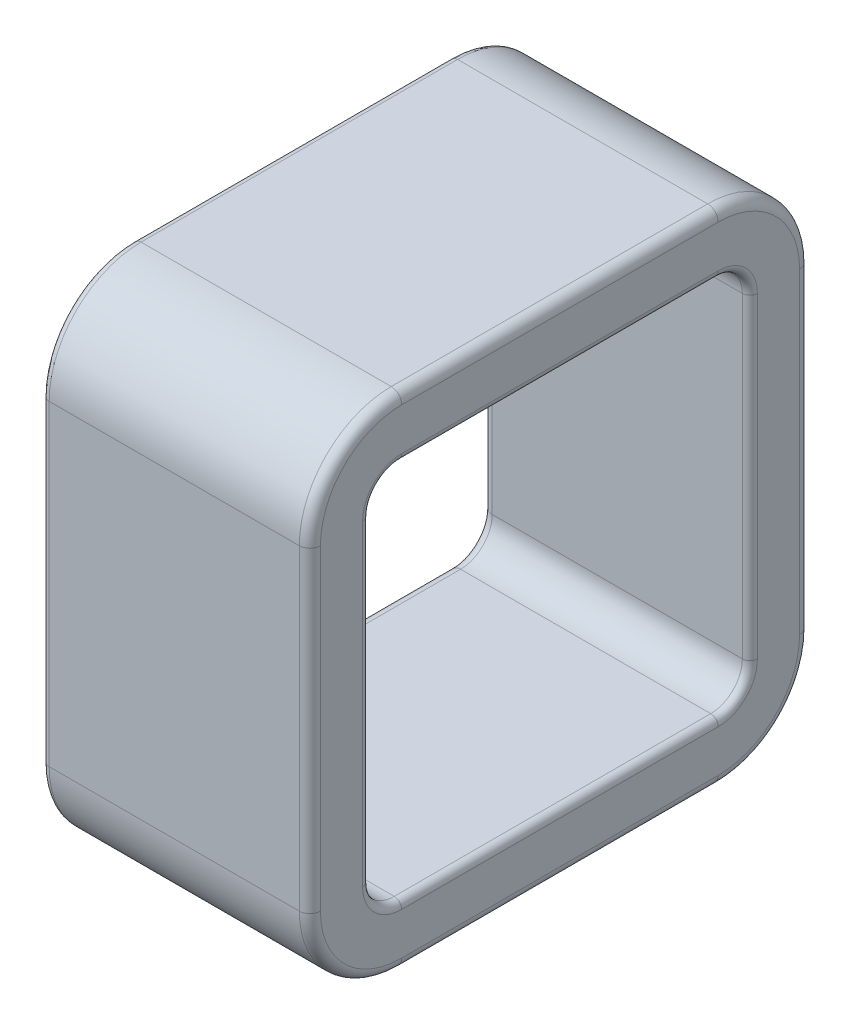
SolidWorks part; units mm, degrees
ref_plane "Front Plane" through (0, 0, 0) normal (0, 0, 1) x (1, 0, 0)
ref_plane "Top Plane" through (0, 0, 0) normal (0, 1, 0) x (1, 0, 0)
ref_plane "Right Plane" through (0, 0, 0) normal (1, 0, 0) x (0, 0, -1)
ref_plane "Plane1" through (72.6, 0, 0) normal (1, 0, 0) x (0, 0, -1)
ref_plane "Plane2" through (0, 8.25, 0) normal (0, 1, 0) x (1, 0, 0)
sketch "Sketch1" plane through (72.6, 0, 0) normal (1, 0, 0) x (0, 0, -1)
  line L0 (-27.5, 17.5) -> (-27.5, -3.5) construction
  line L1 (-25.5, -5.5) -> (-4.5, -5.5) construction
  line L2 (-2.5, 17.5) -> (-2.5, -3.5) construction
  line L3 (-25.5, 19.5) -> (-4.5, 19.5) construction
  line L4 (-27.5, 17.5) -> (-27.5, -3.5) construction
  line L5 (-25.5, -5.5) -> (-4.5, -5.5) construction
  line L6 (-2.5, 17.5) -> (-2.5, -3.5) construction
  line L7 (-25.5, 19.5) -> (-4.5, 19.5) construction
  line L8 (-27.6, 17.5) -> (-27.6, -3.5)
  line L9 (-25.5, -5.6) -> (-4.5, -5.6)
  line L10 (-2.4, 17.5) -> (-2.4, -3.5)
  line L11 (-25.5, 19.6) -> (-4.5, 19.6)
  line L16 (-31.6, 17.5) -> (-31.6, -3.5)
  line L17 (-28.6, 21) -> (-1.4, 21) construction
  line L18 (-31.6, 18) -> (-31.6, -4) construction
  line L19 (-28.6, -7) -> (-1.4, -7) construction
  line L20 (1.6, 18) -> (1.6, -4) construction
  line L21 (-25.5, -9.6) -> (-4.5, -9.6)
  line L22 (1.6, 17.5) -> (1.6, -3.5)
  line L23 (-25.5, 23.6) -> (-4.5, 23.6)
  arc A0 (-27.5, -3.5) -> (-25.5, -5.5) centre (-25.5, -3.5) ccw construction
  arc A1 (-4.5, -5.5) -> (-2.5, -3.5) centre (-4.5, -3.5) ccw construction
  arc A2 (-2.5, 17.5) -> (-4.5, 19.5) centre (-4.5, 17.5) ccw construction
  arc A3 (-25.5, 19.5) -> (-27.5, 17.5) centre (-25.5, 17.5) ccw construction
  arc A4 (-27.5, -3.5) -> (-25.5, -5.5) centre (-25.5, -3.5) ccw construction
  arc A5 (-4.5, -5.5) -> (-2.5, -3.5) centre (-4.5, -3.5) ccw construction
  arc A6 (-2.5, 17.5) -> (-4.5, 19.5) centre (-4.5, 17.5) ccw construction
  arc A7 (-25.5, 19.5) -> (-27.5, 17.5) centre (-25.5, 17.5) ccw construction
  arc A8 (-27.6, -3.5) -> (-25.5, -5.6) centre (-25.5, -3.5) ccw
  arc A9 (-4.5, -5.6) -> (-2.4, -3.5) centre (-4.5, -3.5) ccw
  arc A10 (-2.4, 17.5) -> (-4.5, 19.6) centre (-4.5, 17.5) ccw
  arc A11 (-25.5, 19.6) -> (-27.6, 17.5) centre (-25.5, 17.5) ccw
  arc A16 (-31.6, -4) -> (-28.6, -7) centre (-28.6, -4) ccw construction
  arc A17 (-1.4, -7) -> (1.6, -4) centre (-1.4, -4) ccw construction
  arc A18 (1.6, 18) -> (-1.4, 21) centre (-1.4, 18) ccw construction
  arc A19 (-28.6, 21) -> (-31.6, 18) centre (-28.6, 18) ccw construction
  arc A20 (-31.6, -3.5) -> (-25.5, -9.6) centre (-25.5, -3.5) ccw
  arc A21 (-4.5, -9.6) -> (1.6, -3.5) centre (-4.5, -3.5) ccw
  arc A22 (1.6, 17.5) -> (-4.5, 23.6) centre (-4.5, 17.5) ccw
  arc A23 (-25.5, 23.6) -> (-31.6, 17.5) centre (-25.5, 17.5) ccw
  dimension "D6" = 3
  dimension "D2" = 1.5
  dimension "D3" = 1.5
  dimension "D4" = 4
  dimension "D1" = 0.1
extrude "Boss-Extrude1" add sketch "Sketch1" against normal offset from surface 0.2 and the other way blind 12
sketch "Sketch2" plane through (0, 8.25, 0) normal (0, 1, 0) x (1, 0, 0)
  line L0 (-0.1, -3) -> (-0.1, -27) construction
  line L1 (3, -30.1) -> (62, -30.1) construction
  line L2 (65.1, -27) -> (65.1, -3) construction
  line L3 (62, 0.1) -> (3, 0.1) construction
  line L4 (66.6, 1.6) -> (-1.6, 1.6) construction
  line L5 (-1.6, 1.6) -> (-1.6, -31.6) construction
  line L6 (66.6, 1.6) -> (66.6, -31.6) construction
  line L7 (-1.6, -31.6) -> (66.6, -31.6) construction
  line L8 (-0.1, -3) -> (-0.1, -27)
  line L9 (3, -30.1) -> (62, -30.1)
  line L10 (65.1, -27) -> (65.1, -3)
  line L11 (62, 0.1) -> (3, 0.1)
  line L12 (66.6, 1.6) -> (-1.6, 1.6)
  line L13 (-1.6, 1.6) -> (-1.6, -31.6)
  line L14 (66.6, 1.6) -> (66.6, -31.6)
  line L15 (-1.6, -31.6) -> (66.6, -31.6)
  line L16 (0.65, -3) -> (-1.6, -3)
  line L17 (0.65, -27) -> (-1.6, -27)
  line L20 (57.6, 0.1) -> (57.6, 1.6) construction
  line L21 (7.4, 0.1) -> (7.4, 1.6) construction
  line L23 (59.1, -29.35) -> (59.1, -31.6)
  line L24 (6.4, -29.35) -> (6.4, -31.6)
  line L25 (18.9, -30.1) -> (18.9, -31.6)
  line L26 (37.1, -30.1) -> (37.1, -31.6)
  line L27 (3, -29.35) -> (62, -29.35)
  line L28 (64.35, -27) -> (64.35, -3)
  line L29 (62, -0.65) -> (3, -0.65)
  line L30 (64.35, -27) -> (66.6, -27)
  line L31 (64.35, -3) -> (66.6, -3)
  line L35 (57.6, 0.1) -> (57.6, 1.6)
  line L36 (7.4, 0.1) -> (7.4, 1.6)
  arc A0 (3, 0.1) -> (-0.1, -3) centre (3, -3) ccw construction
  arc A1 (-0.1, -27) -> (3, -30.1) centre (3, -27) ccw construction
  arc A2 (62, -30.1) -> (65.1, -27) centre (62, -27) ccw construction
  arc A3 (65.1, -3) -> (62, 0.1) centre (62, -3) ccw construction
  arc A4 (3, 0.1) -> (-0.1, -3) centre (3, -3) ccw
  arc A5 (-0.1, -27) -> (3, -30.1) centre (3, -27) ccw
  arc A6 (62, -30.1) -> (65.1, -27) centre (62, -27) ccw
  arc A7 (65.1, -3) -> (62, 0.1) centre (62, -3) ccw
  arc A8 (0.65, -27) -> (3, -29.35) centre (3, -27) ccw
  arc A9 (62, -29.35) -> (64.35, -27) centre (62, -27) ccw
  arc A10 (64.35, -3) -> (62, -0.65) centre (62, -3) ccw
  arc A11 (3, -0.65) -> (0.65, -3) centre (3, -3) ccw
  dimension "D1" = 6.5
  dimension "D2" = 6
  dimension "D3" = 19
  dimension "D4" = 28
  dimension "D5" = 0.75
fillet "Fillet2" radius 0.7 16 edges at (66.8, 18.9849, 26.9849) (66.8, 19.6, 15) (66.8, 18.9849, 3.0151) (66.8, 7, 2.4) (66.8, -4.9849, 3.0151) (66.8, 7, 27.6) (66.8, -4.9849, 26.9849) (66.8, -5.6, 15) (84.6, 21.8134, 0.1866) (84.6, 23.6, 15) (84.6, 21.8134, 29.8134) (84.6, 7, 31.6) (84.6, -7.8134, 29.8134) (84.6, -9.6, 15) (84.6, -7.8134, 0.1866) (84.6, 7, -1.6)
fillet "Fillet3" radius 0.5 16 edges at (84.6, 7, 2.4) (84.6, -4.9849, 3.0151) (84.6, -5.6, 15) (84.6, -4.9849, 26.9849) (84.6, 7, 27.6) (84.6, 18.9849, 26.9849) (84.6, 19.6, 15) (84.6, 18.9849, 3.0151) (66.8, -7.8134, 0.1866) (66.8, 7, -1.6) (66.8, 21.8134, 0.1866) (66.8, 23.6, 15) (66.8, 21.8134, 29.8134) (66.8, 7, 31.6) (66.8, -7.8134, 29.8134) (66.8, -9.6, 15)
